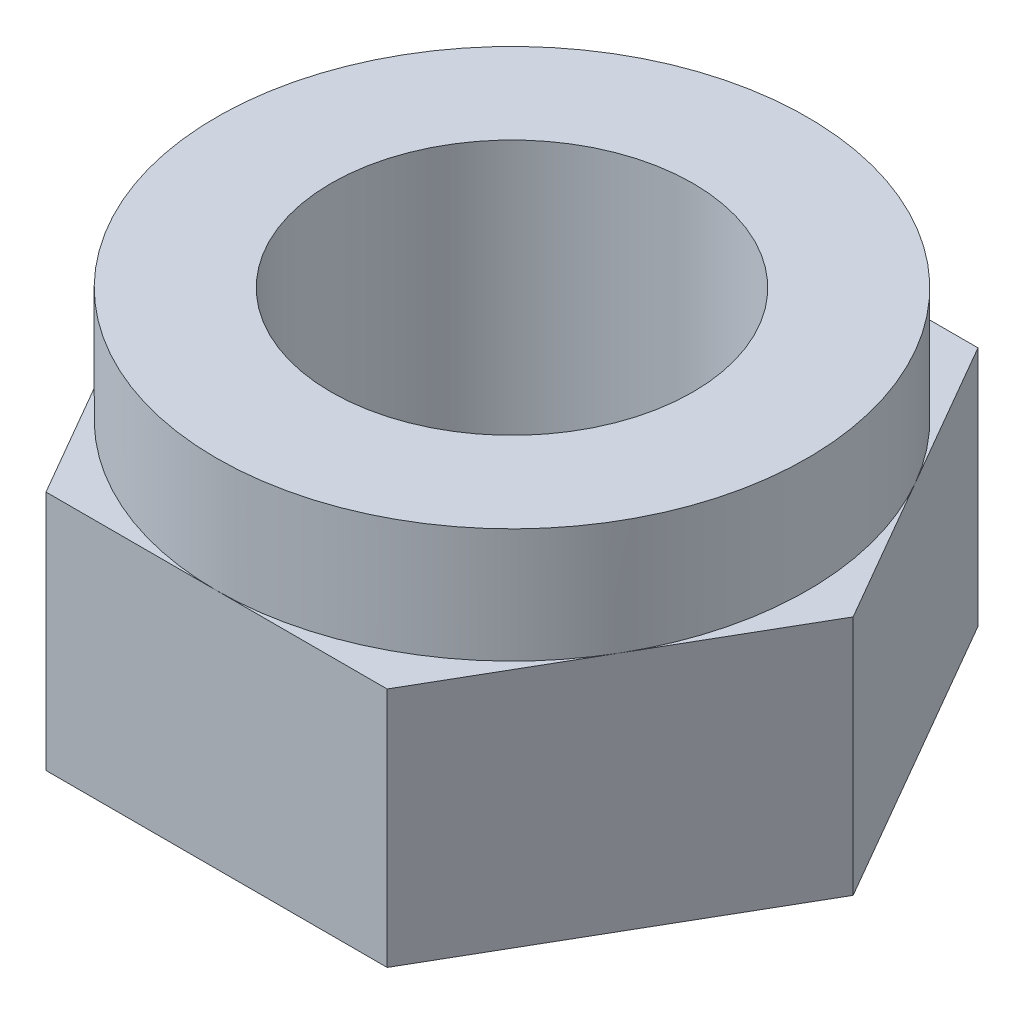
SolidWorks part; units mm, degrees
ref_plane "前视基准面" through (0, 0, 0) normal (0, 0, 1) x (1, 0, 0)
ref_plane "上视基准面" through (0, 0, 0) normal (0, 1, 0) x (1, 0, 0)
ref_plane "右视基准面" through (0, 0, 0) normal (1, 0, 0) x (0, 0, -1)
other "Configuration Table"
sketch "草图1" plane through (0, 0, 0) normal (0, 1, 0) x (1, 0, 0)
  line L1 (5.658, 0) -> (2.829, 4.9)
  line L2 (2.829, 4.9) -> (-2.829, 4.9)
  line L3 (-2.829, 4.9) -> (-5.658, 0)
  line L4 (-5.658, 0) -> (-2.829, -4.9)
  line L5 (-2.829, -4.9) -> (2.829, -4.9)
  line L6 (2.829, -4.9) -> (5.658, 0)
  circle A0 centre (0, 0) radius 4.9 construction
  point P1 (0, 0)
  dimension "D1" = 9.8
extrude "凸台-拉伸1" add sketch "草图1" along normal blind 4
sketch "草图2" plane through (0, 0, 0) normal (0, 1, 0) x (1, 0, 0)
  circle A0 centre (0, 0) radius 4.9 construction
  circle A1 centre (0, 0) radius 4.9
extrude "凸台-拉伸2" add sketch "草图2" along normal blind 1.9 from surface at 4 starting at face at (0, 4, 0)
sketch "草图3" plane through (0, 0, 0) normal (0, 1, 0) x (1, 0, 0)
  circle A0 centre (0, 0) radius 3
  dimension "D1" = 6
extrude "切除-拉伸1" cut sketch "草图3" along normal up to next
